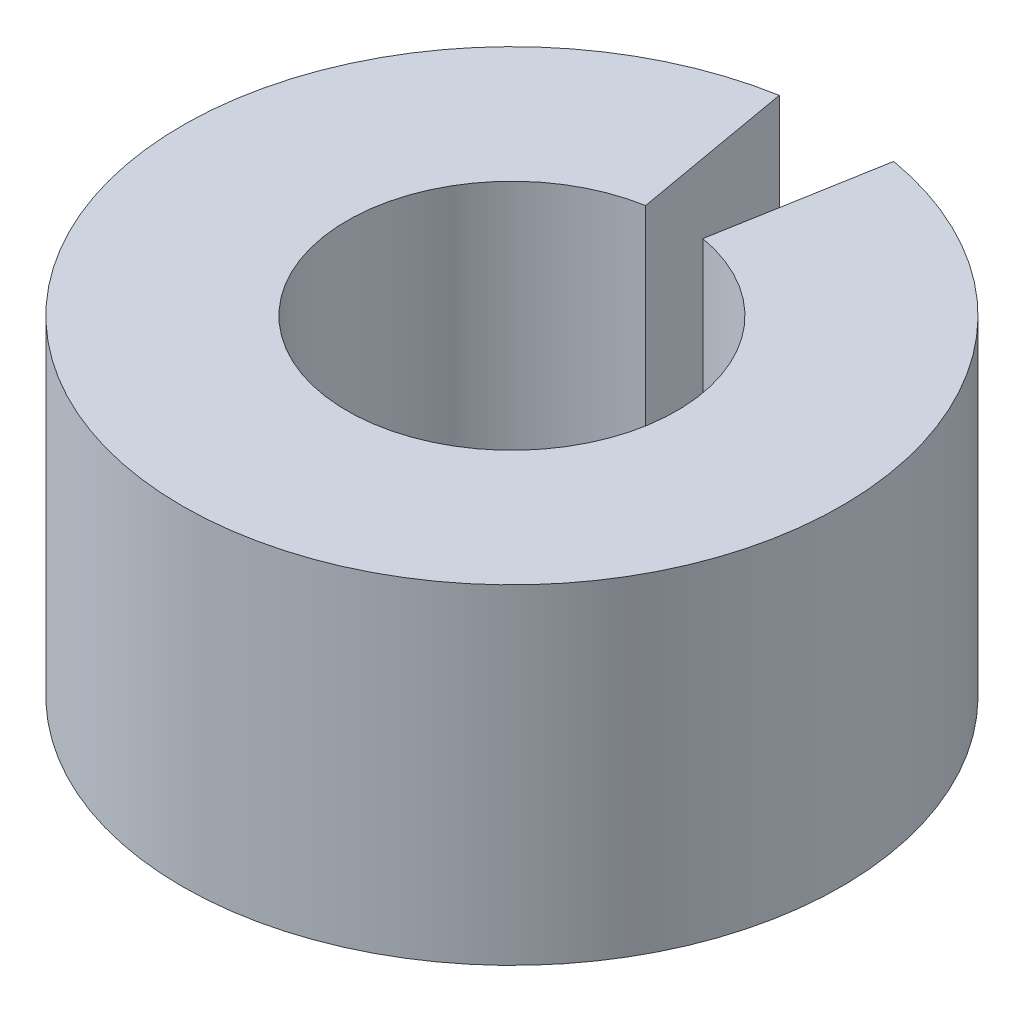
SolidWorks part; units mm, degrees
material "1060 Alloy"
ref_plane "Front Plane" through (0, 0, 0) normal (0, 0, 1) x (1, 0, 0)
ref_plane "Top Plane" through (0, 0, 0) normal (0, 1, 0) x (1, 0, 0)
ref_plane "Right Plane" through (0, 0, 0) normal (1, 0, 0) x (0, 0, -1)
sketch "Sketch1" plane through (0, 0, 0) normal (0, 1, 0) x (1, 0, 0)
  line L1 (0.0868, 0.4924) -> (0.1736, 0.9848)
  line L2 (-0.0868, 0.4924) -> (-0.1736, 0.9848)
  arc A0 (-0.0868, 0.4924) -> (0.0868, 0.4924) centre (0, 0) ccw
  arc A1 (-0.1736, 0.9848) -> (0.1736, 0.9848) centre (0, 0) ccw
  dimension "D1" = 1
  dimension "D2" = 2
extrude "Boss-Extrude1" add sketch "Sketch1" along normal blind 1
